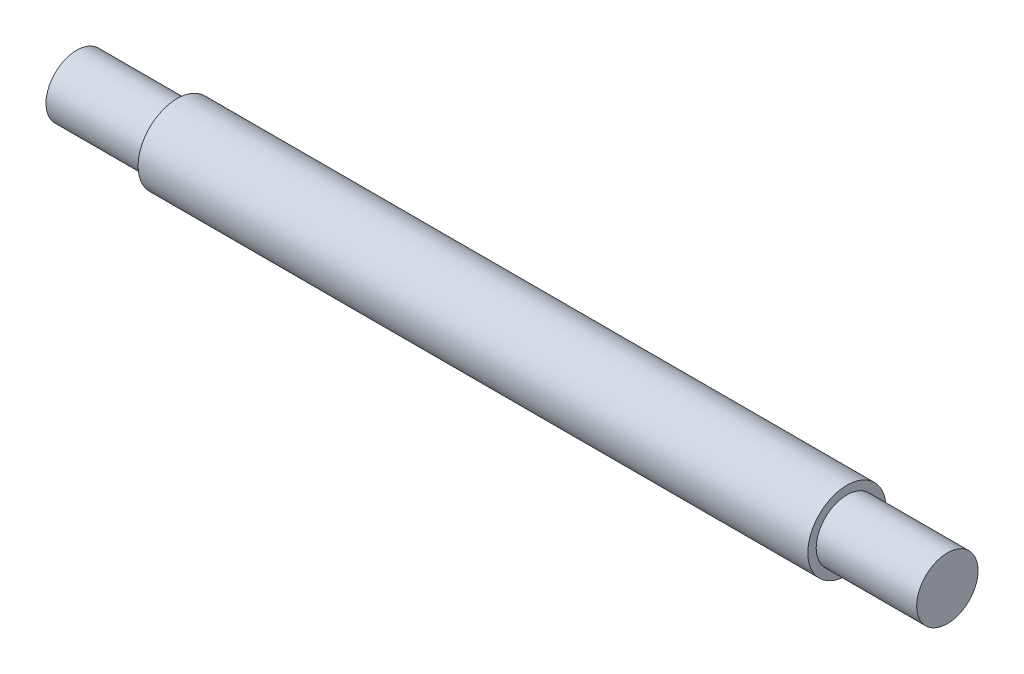
SolidWorks part; units mm, degrees
ref_plane "Front Plane" through (0, 0, 0) normal (0, 0, 1) x (1, 0, 0)
ref_plane "Top Plane" through (0, 0, 0) normal (0, 1, 0) x (1, 0, 0)
ref_plane "Right Plane" through (0, 0, 0) normal (1, 0, 0) x (0, 0, -1)
sketch "Sketch1" plane through (0, 0, 0) normal (0, 1, 0) x (1, 0, 0)
  line L0 (0, 0) -> (156, 0)
  line L1 (156, 0) -> (156, 5.5)
  line L2 (156, 5.5) -> (138, 5.5)
  line L3 (138, 5.5) -> (138, 7)
  line L4 (138, 7) -> (18, 7)
  line L5 (18, 7) -> (18, 5.5)
  line L6 (18, 5.5) -> (0, 5.5)
  line L7 (0, 5.5) -> (0, 0)
  point P5 (156.3416, 0)
  point P10 (18, 11.1377)
  dimension "D1" = 18
  dimension "D2" = 120
  dimension "D3" = 18
  dimension "D4" = 5.5
  dimension "D5" = 7
revolve "Revolve1" add sketch "Sketch1" angle 360 about L0
